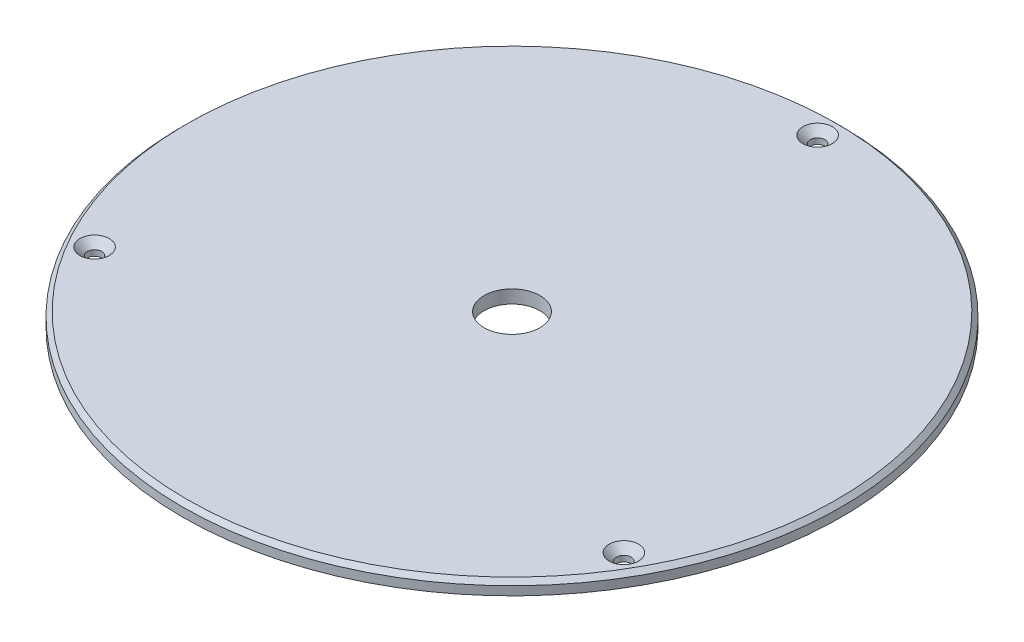
SolidWorks part; units mm, degrees
material "PETG"
ref_plane "Спереди" through (0, 0, 0) normal (0, 0, 1) x (1, 0, 0)
ref_plane "Сверху" through (0, 0, 0) normal (0, 1, 0) x (1, 0, 0)
ref_plane "Справа" through (0, 0, 0) normal (1, 0, 0) x (0, 0, -1)
sketch "Эскиз1" plane through (0, 0, 0) normal (0, 1, 0) x (1, 0, 0)
  circle A0 centre (0, 0) radius 75
  dimension "D1" = 150
extrude "Бобышка-Вытянуть1" add sketch "Эскиз1" along normal blind 3
sketch "Эскиз2" plane through (0, 3, 0) normal (0, 1, 0) x (1, 0, 0)
  line L0 (0, 0) -> (-50000, 0) construction
  line L1 (0, 0) -> (0, 50000) construction
  circle A0 centre (0, 69.55) radius 1.65
  dimension "D2" = 3.3
  dimension "D1" = 69.55
extrude "Вырез-Вытянуть1" cut sketch "Эскиз2" against normal through all
chamfer "Фаска1" distance 1.7 angle 45 1 edges at (0, 3, -67.9)
pattern_circular "Круговой массив1" count 3 over 360 about axis through (0, 0, 0) along (0, 1, 0) of "Вырез-Вытянуть1", "Фаска1"
sketch "Эскиз3" plane through (0, 3, 0) normal (0, 1, 0) x (1, 0, 0)
  circle A0 centre (0, 0) radius 6.35
  dimension "D1" = 12.7
extrude "Вырез-Вытянуть2" cut sketch "Эскиз3" against normal through all
chamfer "Фаска2" distance 1 angle 45 1 edges at (0, 3, 75)
